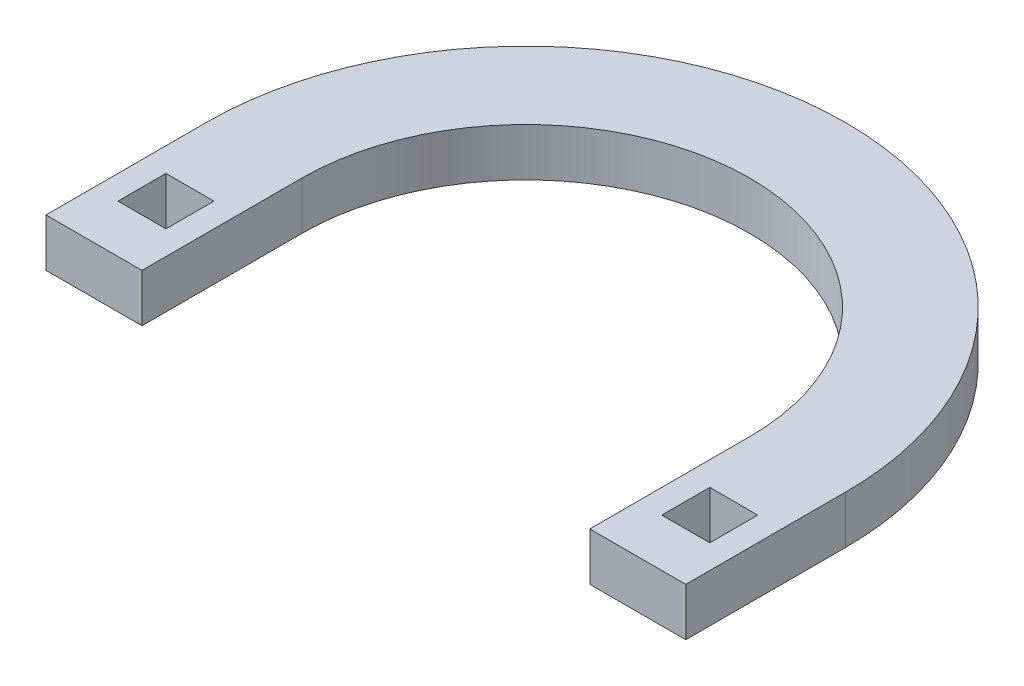
SolidWorks part; units mm, degrees
ref_plane "Front Plane" through (0, 0, 0) normal (0, 0, 1) x (1, 0, 0)
ref_plane "Top Plane" through (0, 0, 0) normal (0, 1, 0) x (1, 0, 0)
ref_plane "Right Plane" through (0, 0, 0) normal (1, 0, 0) x (0, 0, -1)
sketch "Sketch1" plane through (0, 0, 0) normal (0, 1, 0) x (1, 0, 0)
  line L8 (-20, 0) -> (-20, -10)
  line L9 (-20, -10) -> (-14, -10)
  line L10 (-14, 0) -> (-14, -10)
  line L12 (14, 0) -> (14, -10)
  line L13 (14, -10) -> (20, -10)
  line L14 (20, 0) -> (20, -10)
  arc A5 (-20, 0) -> (20, 0) centre (0, 0) cw
  arc A6 (-14, 0) -> (14, 0) centre (0, 0) cw
  dimension "D1" = 20
  dimension "D2" = 14
  dimension "D3" = 6
  dimension "D4" = 6
  dimension "D5" = 10
  dimension "D6" = 10
extrude "Boss-Extrude1" add sketch "Sketch1" along normal blind 3
extrude "Cut-Extrude1" cut sketch "Sketch2" against normal through all
sketch "Sketch2" plane through (-39.0911, 6, -26.5235) normal (0, 1, 0) x (1, 0, 0)
  line L1 (20.5911, -30.5235) -> (23.5911, -30.5235)
  line L2 (20.5911, -30.5235) -> (20.5911, -33.5235)
  line L3 (20.5911, -33.5235) -> (23.5911, -33.5235)
  line L4 (23.5911, -30.5235) -> (23.5911, -33.5235)
  line L7 (54.5911, -33.5235) -> (57.5911, -33.5235)
  line L8 (54.5911, -33.5235) -> (54.5911, -30.5235)
  line L9 (54.5911, -30.5235) -> (57.5911, -30.5235)
  line L10 (57.5911, -33.5235) -> (57.5911, -30.5235)
